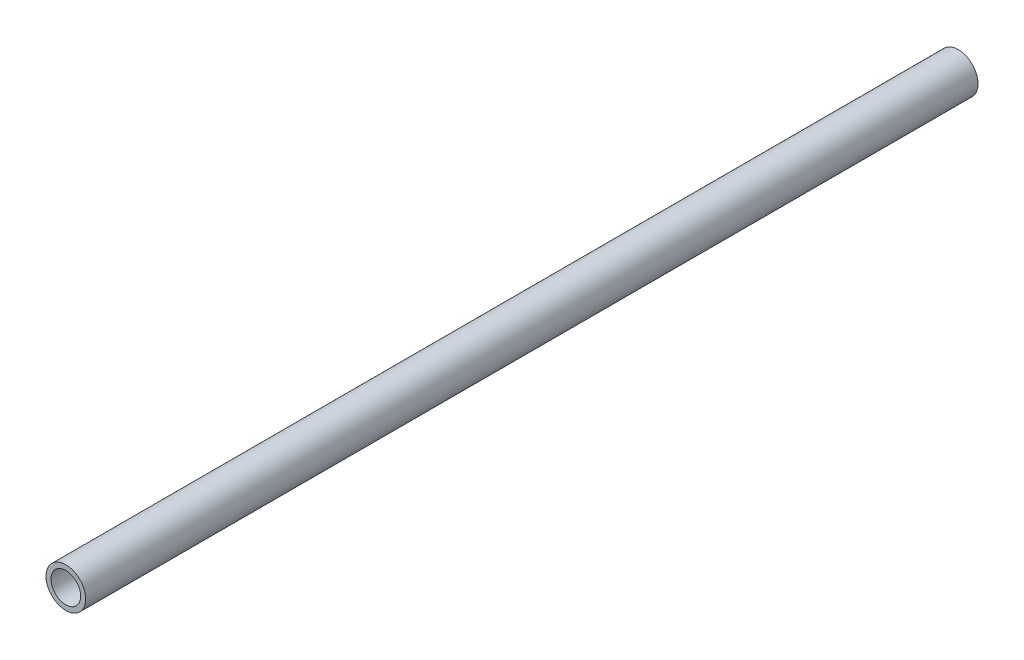
SolidWorks part; units mm, degrees
ref_plane "Ön Düzlem" through (0, 0, 0) normal (0, 0, 1) x (1, 0, 0)
ref_plane "Üst Düzlem" through (0, 0, 0) normal (0, 1, 0) x (1, 0, 0)
ref_plane "Sağ Düzlem" through (0, 0, 0) normal (1, 0, 0) x (0, 0, -1)
sketch "Çizim1" plane through (0, 0, 0) normal (0, 0, 1) x (1, 0, 0)
  circle A0 centre (0, 0) radius 3
  circle A1 centre (0, 0) radius 4
  dimension "D1" = 8
  dimension "D2" = 6
extrude "Yükseklik-Ekstrüzyon1" add sketch "Çizim1" along normal blind 180
